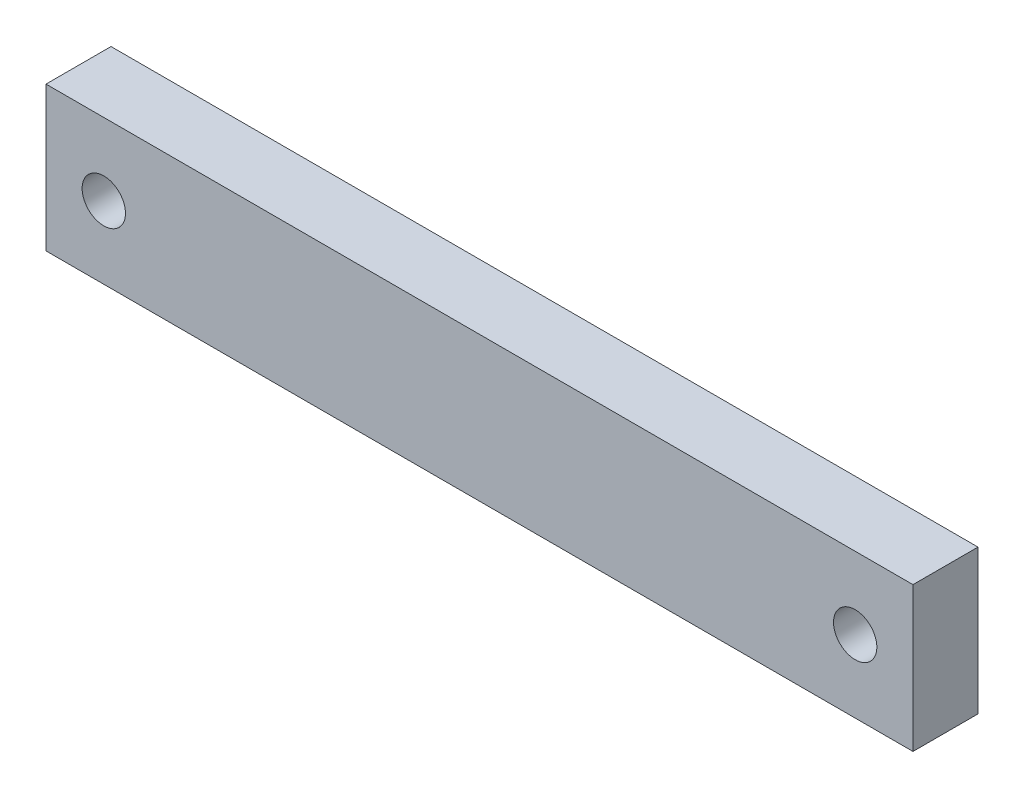
SolidWorks part; units mm, degrees
material "Acrylic (Medium-high impact)"
ref_plane "Front Plane" through (0, 0, 0) normal (0, 0, 1) x (1, 0, 0)
ref_plane "Top Plane" through (0, 0, 0) normal (0, 1, 0) x (1, 0, 0)
ref_plane "Right Plane" through (0, 0, 0) normal (1, 0, 0) x (0, 0, -1)
sketch "Sketch1" plane through (0, 0, 0) normal (0, 0, 1) x (1, 0, 0)
  line L1 (30, -5) -> (-30, -5)
  line L2 (30, -5) -> (30, 5)
  line L3 (30, 5) -> (-30, 5)
  line L4 (-30, -5) -> (-30, 5)
  line L5 (30, -5) -> (-30, 5) construction
  line L6 (30, 5) -> (-30, -5) construction
  circle A0 centre (-26, 0) radius 1.5
  circle A1 centre (26, 0) radius 1.5
  point P0 (0, 0)
  dimension "D3" = 3
  dimension "D4" = 3
  dimension "D1" = 10
  dimension "D2" = 60
  dimension "3" = 4
  dimension "4" = 4
extrude "Boss-Extrude1" add sketch "Sketch1" along normal blind 4.5
